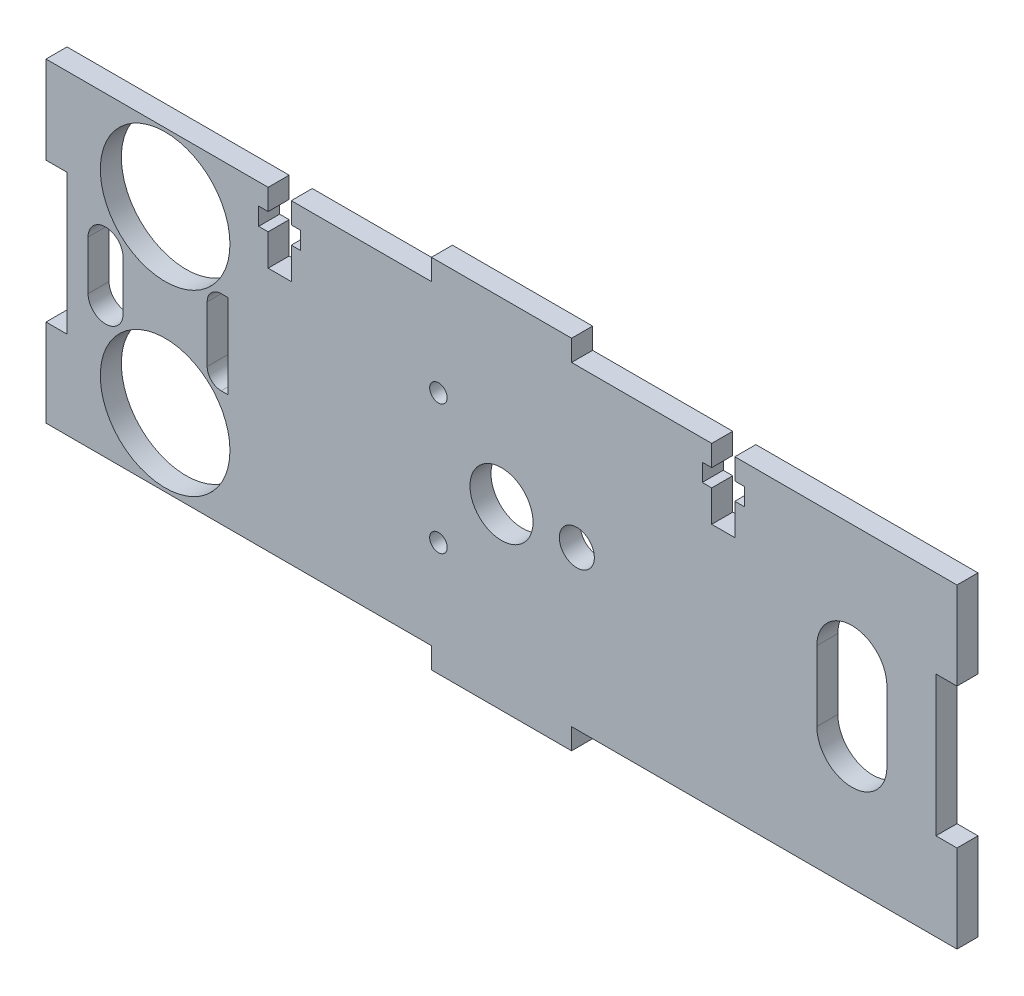
SolidWorks part; units mm, degrees
ref_plane "Front Plane" through (0, 0, 0) normal (0, 0, 1) x (1, 0, 0)
ref_plane "Top Plane" through (0, 0, 0) normal (0, 1, 0) x (1, 0, 0)
ref_plane "Right Plane" through (0, 0, 0) normal (1, 0, 0) x (0, 0, -1)
sketch "Sketch1" plane through (0, 0, 0) normal (0, 0, 1) x (1, 0, 0)
  line L0 (-10, -22.5) -> (-65, -22.5)
  line L1 (65, -22.5) -> (10, -22.5)
  line L2 (65, -22.5) -> (65, -10)
  line L3 (65, 22.5) -> (33.3, 22.5)
  line L4 (-65, -22.5) -> (-65, -10)
  line L5 (65, -22.5) -> (-65, 22.5) construction
  line L6 (65, 22.5) -> (-65, -22.5) construction
  line L8 (-10, -22.5) -> (-10, -25.5)
  line L9 (-10, -25.5) -> (10, -25.5)
  line L10 (10, -22.5) -> (10, -25.5)
  line L11 (0, -55) -> (0, 55) construction
  line L12 (-62, -10) -> (-65, -10)
  line L13 (-62, -10) -> (-62, 10)
  line L14 (-62, 10) -> (-65, 10)
  line L16 (-62, -10) -> (-65, 10) construction
  line L17 (-62, 10) -> (-65, -10) construction
  line L18 (62, 10) -> (65, 10)
  line L20 (62, -10) -> (65, -10)
  line L21 (62, -10) -> (62, 10)
  line L22 (-65, 10) -> (-65, 22.5)
  line L23 (65, 10) -> (65, 22.5)
  line L24 (-56.5, 3.5) -> (-56.5, -3.5) construction
  line L29 (-54, 3.5) -> (-54, -3.5)
  line L30 (-59, 3.5) -> (-59, -3.5)
  line L31 (-39, -6) -> (-40, -6)
  line L32 (-39, -6) -> (-39, 6)
  line L33 (-39, 6) -> (-40, 6)
  line L34 (-42, -4) -> (-42, 4)
  line L35 (-39, -6) -> (-42, 6) construction
  line L36 (-39, 6) -> (-42, -6) construction
  line L37 (55, 0) -> (-55, 0) construction
  line L40 (-10, 22.5) -> (-10, 25.5)
  line L41 (-10, 25.5) -> (10, 25.5)
  line L42 (10, 22.5) -> (10, 25.5)
  line L43 (-10, 22.5) -> (-30, 22.5)
  line L44 (33.3, 12.5) -> (30, 12.5)
  line L46 (-33.3, 22.5) -> (-33.3, 19.5)
  line L47 (-33.3, 12.5) -> (-30, 12.5)
  line L48 (-30, 22.5) -> (-30, 19.5)
  line L49 (-34.65, 19.5) -> (-33.3, 19.5)
  line L50 (-34.65, 19.5) -> (-34.65, 17)
  line L51 (-34.65, 17) -> (-33.3, 17)
  line L52 (-28.65, 19.5) -> (-28.65, 17)
  line L53 (30, 22.5) -> (30, 19.5)
  line L55 (33.3, 22.5) -> (33.3, 19.5)
  line L56 (34.65, 17) -> (33.3, 17)
  line L57 (28.65, 19.5) -> (28.65, 17)
  line L58 (34.65, 19.5) -> (33.3, 19.5)
  line L59 (34.65, 19.5) -> (34.65, 17)
  line L60 (-33.3, 22.5) -> (-65, 22.5)
  line L61 (-30, 19.5) -> (-28.65, 19.5)
  line L62 (-33.3, 17) -> (-33.3, 12.5)
  line L63 (-30, 17) -> (-28.65, 17)
  line L64 (-30, 17) -> (-30, 12.5)
  line L65 (30, 22.5) -> (10, 22.5)
  line L66 (30, 19.5) -> (28.65, 19.5)
  line L67 (30, 17) -> (30, 12.5)
  line L68 (33.3, 17) -> (33.3, 12.5)
  line L69 (30, 17) -> (28.65, 17)
  line L70 (50, -5) -> (50, 5) construction
  line L75 (45, -5) -> (45, 5)
  line L76 (55, -5) -> (55, 5)
  circle A0 centre (-48, 12.75) radius 9.25
  circle A1 centre (-48, -12.75) radius 9.25
  circle A6 centre (0, 0) radius 4.5
  circle A7 centre (10.75, 0) radius 2.5
  arc A10 (-54, 3.5) -> (-59, 3.5) centre (-56.5, 3.5) ccw
  arc A11 (-59, -3.5) -> (-54, -3.5) centre (-56.5, -3.5) ccw
  arc A12 (-40, -6) -> (-42, -4) centre (-40, -4) cw
  arc A13 (-40, 6) -> (-42, 4) centre (-40, 4) ccw
  circle A14 centre (-9, 9.25) radius 1.25
  circle A15 centre (-9, -9.25) radius 1.25
  arc A16 (45, -5) -> (55, -5) centre (50, -5) ccw
  arc A17 (55, 5) -> (45, 5) centre (50, 5) ccw
  point P0 (0, 0)
  point P10 (-63.5, 0)
  point P26 (-56.5, 0)
  point P49 (-40.5, 0)
  point P83 (50, 0)
  point P88 (0, 0)
  dimension "D8" = 18.5
  dimension "D15" = 2
  dimension "D16" = 9
  dimension "D17" = 5
  dimension "D22" = 2.5
  dimension "D12" = 2.5
  dimension "D35" = 5
  dimension "D1" = 130
  dimension "D2" = 45
  dimension "D3" = 3
  dimension "D4" = 20
  dimension "D5" = 55
  dimension "D6" = 20
  dimension "D7" = 3
  dimension "D9" = 17
  dimension "D10" = 25.5
  dimension "D11" = 12.75
  dimension "D13" = 7
  dimension "D14" = 6
  dimension "D18" = 10.75
  dimension "D19" = 3
  dimension "D20" = 12
  dimension "D21" = 6
  dimension "D23" = 9
  dimension "D24" = 9.25
  dimension "D25" = 20
  dimension "D26" = 3
  dimension "D27" = 55
  dimension "D28" = 3.3
  dimension "D29" = 10
  dimension "D30" = 2.5
  dimension "D31" = 6
  dimension "D32" = 3
  dimension "D33" = 1.35
  dimension "D34" = 20
  dimension "D36" = 10
  dimension "D37" = 10
extrude "Boss-Extrude1" add sketch "Sketch1" along normal blind 3
